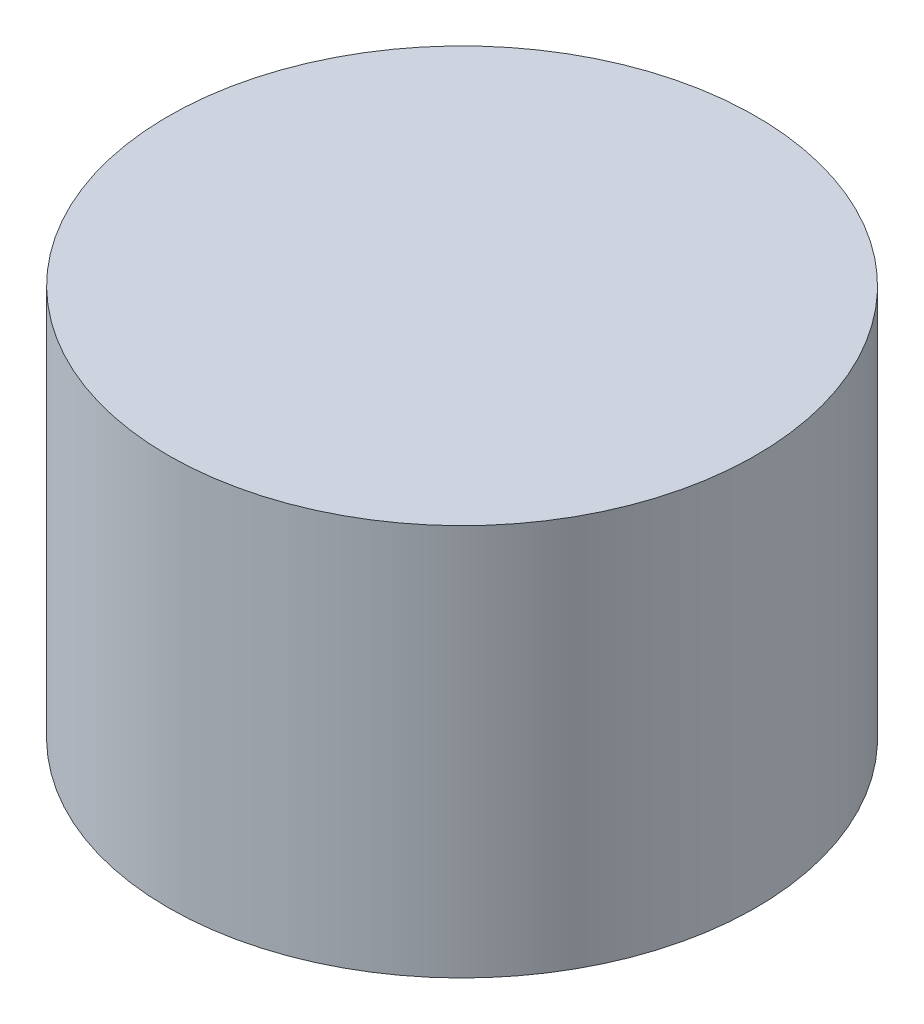
SolidWorks part; units mm, degrees
ref_plane "Front Plane" through (0, 0, 0) normal (0, 0, 1) x (1, 0, 0)
ref_plane "Top Plane" through (0, 0, 0) normal (0, 1, 0) x (1, 0, 0)
ref_plane "Right Plane" through (0, 0, 0) normal (1, 0, 0) x (0, 0, -1)
sketch "Sketch1" plane through (0, 0, 0) normal (0, 1, 0) x (1, 0, 0)
  circle A0 centre (0, 0) radius 9
  dimension "D1" = 18
extrude "Boss-Extrude1" add sketch "Sketch1" along normal blind 12
